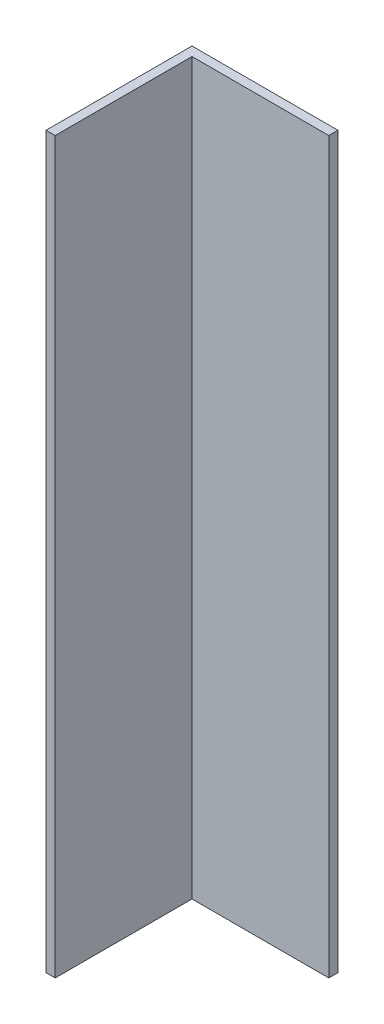
SolidWorks part; units mm, degrees
ref_plane "Front Plane" through (0, 0, 0) normal (0, 0, 1) x (1, 0, 0)
ref_plane "Top Plane" through (0, 0, 0) normal (0, 1, 0) x (1, 0, 0)
ref_plane "Right Plane" through (0, 0, 0) normal (1, 0, 0) x (0, 0, -1)
sketch "Sketch1" plane through (0, 0, 0) normal (0, 1, 0) x (1, 0, 0)
  line L1 (0, 0) -> (25.4, 0)
  line L2 (0, 0) -> (0, -25.4)
  line L3 (0, -25.4) -> (25.4, -25.4)
  line L4 (25.4, 0) -> (25.4, -25.4)
extrude "Boss-Extrude1" add sketch "Sketch1" along normal blind 127
sketch "Sketch2" plane through (0, 127, 0) normal (0, 1, 0) x (1, 0, 0)
  line L0 (25.4, -25.4) -> (25.4, 0) construction
  line L1 (25.4, -1.5875) -> (1.5875, -1.5875)
  line L2 (25.4, -1.5875) -> (25.4, -25.4)
  line L3 (25.4, -25.4) -> (1.5875, -25.4)
  line L4 (1.5875, -1.5875) -> (1.5875, -25.4)
  line L5 (0, -25.4) -> (25.4, -25.4) construction
  line L6 (25.4, 0) -> (0, 0) construction
  line L7 (0, 0) -> (0, -25.4) construction
  dimension "D1" = 1.5875
  dimension "D2" = 1.5875
extrude "Cut-Extrude1" cut sketch "Sketch2" against normal through all
